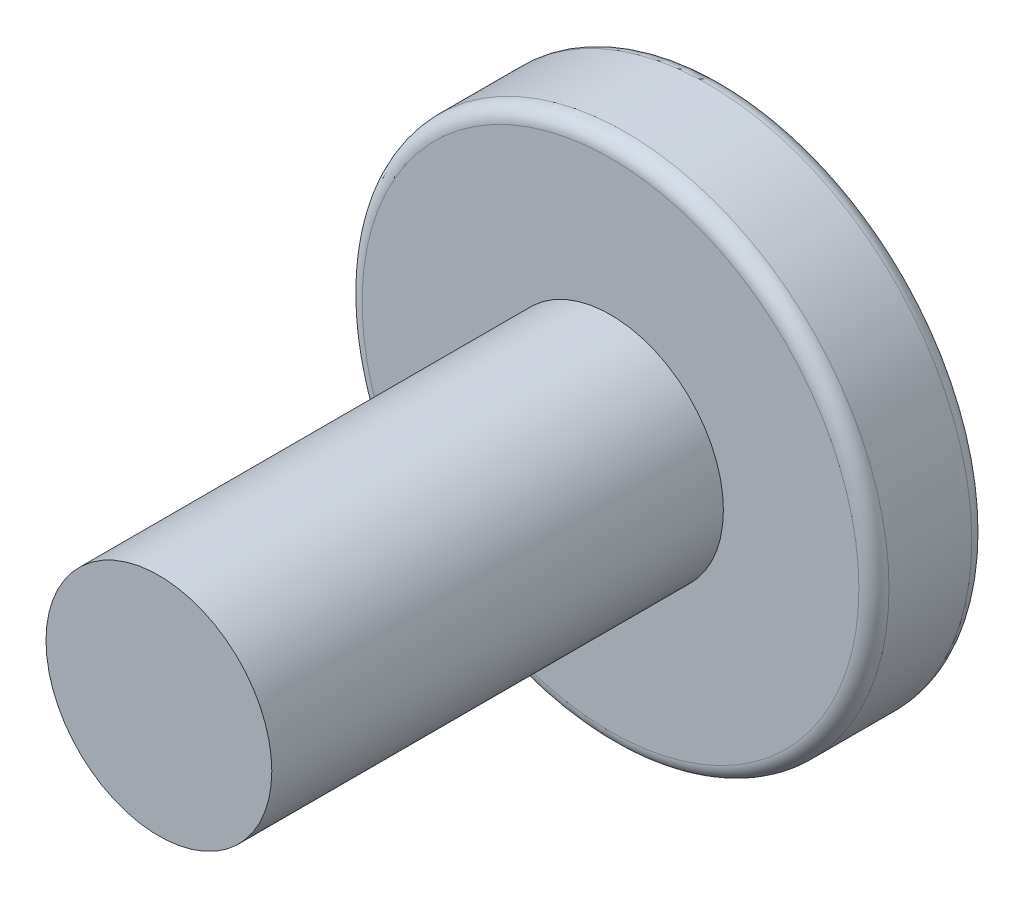
SolidWorks part; units mm, degrees
material "AISI 304"
ref_plane "前视基准面" through (0, 0, 0) normal (0, 0, 1) x (1, 0, 0)
ref_plane "上视基准面" through (0, 0, 0) normal (0, 1, 0) x (1, 0, 0)
ref_plane "右视基准面" through (0, 0, 0) normal (1, 0, 0) x (0, 0, -1)
other "Configuration Table"
sketch "草图1" plane through (0, 0, 0) normal (0, 0, 1) x (1, 0, 0)
  circle A0 centre (0, 0) radius 3.5
  dimension "D1" = 7
extrude "凸台-拉伸1" add sketch "草图1" along normal blind 1.5
sketch "草图2" plane through (0, 0, 1.5) normal (0, 0, 1) x (1, 0, 0)
  circle A1 centre (0, 0) radius 1.5
  dimension "D2" = 3
extrude "凸台-拉伸2" add sketch "草图2" along normal blind 6
fillet "圆角1" radius 0.2 2 edges at (3.5, 0, 0) (3.5, 0, 1.5)
sketch "草图3" plane through (0, 0, 0) normal (0, 0, -1) x (-1, 0, 0)
  line L0 (0, 0) -> (1.1547, 0) construction
  line L1 (1.1547, 0) -> (0.5774, 1)
  line L2 (0.5774, 1) -> (-0.5774, 1)
  line L3 (-0.5774, 1) -> (-1.1547, 0)
  line L4 (-1.1547, 0) -> (-0.5774, -1)
  line L5 (-0.5774, -1) -> (0.5774, -1)
  line L6 (0.5774, -1) -> (1.1547, 0)
  circle A0 centre (0, 0) radius 1 construction
  dimension "D1" = 2
extrude "切除-拉伸1" cut sketch "草图3" against normal blind 1.5
